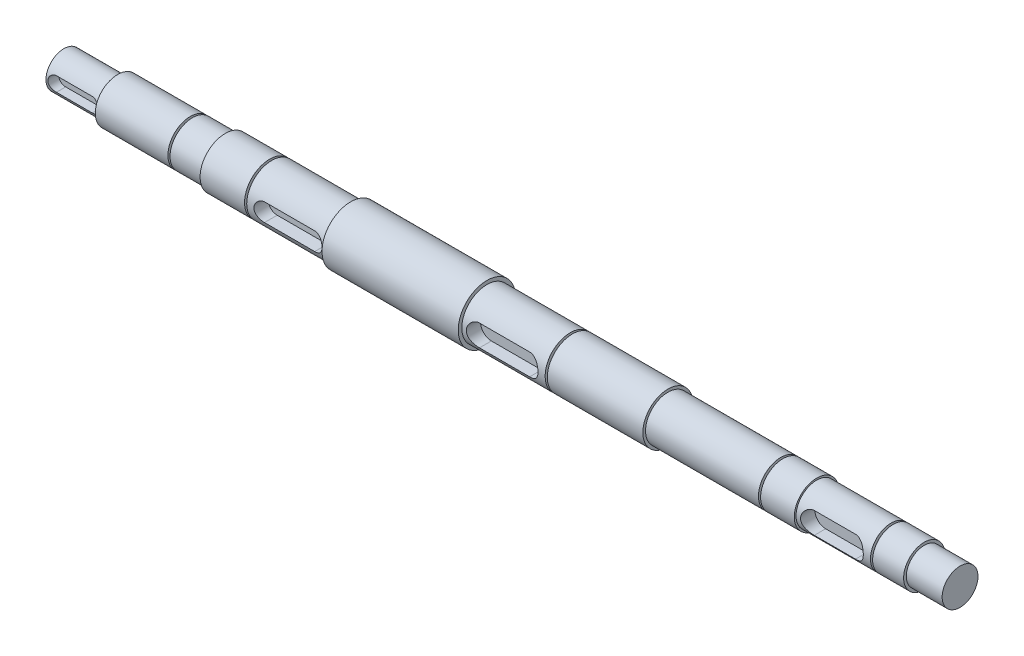
SolidWorks part; units mm, degrees
ref_plane "Front Plane" through (0, 0, 0) normal (0, 0, 1) x (1, 0, 0)
ref_plane "Top Plane" through (0, 0, 0) normal (0, 1, 0) x (1, 0, 0)
ref_plane "Right Plane" through (0, 0, 0) normal (1, 0, 0) x (0, 0, -1)
sketch "Sketch1" plane through (0, 0, 0) normal (1, 0, 0) x (0, 0, -1)
  circle A0 centre (0, 0) radius 10
  dimension "D1" = 20
extrude "Boss-Extrude1" add sketch "Sketch1" along normal blind 30
sketch "Sketch2" plane through (30, 0, 0) normal (1, 0, 0) x (0, 0, -1)
  circle A0 centre (0, 0) radius 12.5
  circle A2 centre (0, 0) radius 10 construction
  dimension "D1" = 25
extrude "Boss-Extrude5" add sketch "Sketch2" along normal blind 60
sketch "Sketch5" plane through (90, 0, 0) normal (1, 0, 0) x (0, 0, -1)
  circle A0 centre (0, 0) radius 14
  dimension "D1" = 28
extrude "Boss-Extrude8" add sketch "Sketch5" along normal blind 70
sketch "Sketch7" plane through (160, 0, 0) normal (1, 0, 0) x (0, 0, -1)
  circle A0 centre (0, 0) radius 16
  dimension "D1" = 32
extrude "Boss-Extrude9" add sketch "Sketch7" along normal blind 76
sketch "Sketch8" plane through (236, 0, 0) normal (1, 0, 0) x (0, 0, -1)
  circle A0 centre (0, 0) radius 14
  dimension "D1" = 28
extrude "Boss-Extrude13" add sketch "Sketch8" along normal blind 24
sketch "Sketch12" plane through (260, 0, 0) normal (1, 0, 0) x (0, 0, -1)
  circle A0 centre (0, 0) radius 12.5
  dimension "D1" = 25
extrude "Boss-Extrude15" add sketch "Sketch12" along normal blind 150
sketch "Sketch14" plane through (410, 0, 0) normal (1, 0, 0) x (0, 0, -1)
  circle A0 centre (0, 0) radius 11.5
  dimension "D1" = 23
extrude "Boss-Extrude16" add sketch "Sketch14" along normal blind 70
sketch "Sketch15" plane through (480, 0, 0) normal (1, 0, 0) x (0, 0, -1)
  circle A1 centre (0, 0) radius 10
  dimension "D1" = 20
extrude "Boss-Extrude17" add sketch "Sketch15" along normal blind 20
ref_plane "Plane1" through (0, 0, 10) normal (0, 0, 1) x (1, 0, 0)
sketch "Sketch16" plane through (0, 0, 10) normal (0, 0, 1) x (1, 0, 0)
  line L0 (0, 0) -> (30, 0) construction
  line L1 (30, 12.5) -> (30, -12.5) construction
  line L2 (5, 0) -> (25, 0) construction
  line L3 (5, 4) -> (25, 4)
  line L4 (5, -4) -> (25, -4)
  arc A0 (5, 4) -> (5, -4) centre (5, 0) ccw
  arc A1 (25, -4) -> (25, 4) centre (25, 0) ccw
  point P7 (15, 0)
  dimension "D1" = 20
  dimension "D2" = 5
  dimension "D3" = 8
extrude "Cut-Extrude1" cut sketch "Sketch16" against normal blind 6
ref_plane "Plane2" through (0, 0, 14) normal (0, 0, 1) x (1, 0, 0)
sketch "Sketch17" plane through (0, 0, 14) normal (0, 0, 1) x (1, 0, 0)
  line L0 (90, 0) -> (160, 0) construction
  line L1 (90, 14) -> (90, -14) construction
  line L2 (160, 16) -> (160, -16) construction
  line L3 (125, 0) -> (153, 0) construction
  line L4 (125, 5) -> (153, 5)
  line L5 (125, -5) -> (153, -5)
  arc A0 (125, 5) -> (125, -5) centre (125, 0) ccw
  arc A1 (153, -5) -> (153, 5) centre (153, 0) ccw
  point P8 (139, 0)
  dimension "D1" = 28
  dimension "D2" = 35
  dimension "D3" = 10
extrude "Cut-Extrude2" cut sketch "Sketch17" against normal blind 8
sketch "Sketch18" plane through (236, 0, 0) normal (1, 0, 0) x (0, 0, -1)
  circle A0 centre (0, 0) radius 14
extrude "Cut-Extrude3" cut sketch "Sketch18" along normal up to surface (264 mm away) up to face at (500, 0, -10)
sketch "Sketch19" plane through (236, 0, 0) normal (1, 0, 0) x (0, 0, -1)
  circle A0 centre (0, 0) radius 14
  dimension "D1" = 28
extrude "Boss-Extrude18" add sketch "Sketch19" along normal blind 45
sketch "Sketch20" plane through (281, 0, 0) normal (1, 0, 0) x (0, 0, -1)
  circle A0 centre (0, 0) radius 12.5
  dimension "D1" = 25
extrude "Boss-Extrude19" add sketch "Sketch20" along normal blind 139
sketch "Sketch21" plane through (420, 0, 0) normal (1, 0, 0) x (0, 0, -1)
  circle A0 centre (0, 0) radius 11.5
  dimension "D1" = 23
extrude "Boss-Extrude20" add sketch "Sketch21" along normal blind 60
sketch "Sketch22" plane through (480, 0, 0) normal (1, 0, 0) x (0, 0, -1)
  circle A0 centre (0, 0) radius 10
  dimension "D1" = 20
extrude "Boss-Extrude21" add sketch "Sketch22" along normal blind 20
ref_plane "Plane3" through (0, 0, 14) normal (0, 0, 1) x (1, 0, 0)
sketch "Sketch24" plane through (0, 0, 14) normal (0, 0, 1) x (1, 0, 0)
  line L0 (236, 0) -> (281, 0) construction
  line L1 (236, -16) -> (236, 16) construction
  line L2 (281, -12.5) -> (281, 12.5) construction
  line L3 (244.5, 0) -> (272.5, 0) construction
  line L4 (244.5, 6) -> (272.5, 6)
  line L5 (244.5, -6) -> (272.5, -6)
  arc A0 (244.5, 6) -> (244.5, -6) centre (244.5, 0) ccw
  arc A1 (272.5, -6) -> (272.5, 6) centre (272.5, 0) ccw
  point P8 (258.5, 0)
  dimension "D1" = 28
  dimension "D2" = 8.5
  dimension "D3" = 12
extrude "Cut-Extrude4" cut sketch "Sketch24" against normal blind 8
ref_plane "Plane4" through (0, 0, 11.5) normal (0, 0, 1) x (1, 0, 0)
sketch "Sketch25" plane through (0, 0, 11.5) normal (0, 0, 1) x (1, 0, 0)
  line L0 (420, 0) -> (480, 0) construction
  line L1 (420, -11.5) -> (420, 11.5) construction
  line L2 (480, -10) -> (480, 10) construction
  line L3 (428.5, 0) -> (451.5, 0) construction
  line L4 (428.5, 6) -> (451.5, 6)
  line L5 (428.5, -6) -> (451.5, -6)
  arc A0 (428.5, 6) -> (428.5, -6) centre (428.5, 0) ccw
  arc A1 (451.5, -6) -> (451.5, 6) centre (451.5, 0) ccw
  point P8 (440, 0)
  dimension "D1" = 23
  dimension "D2" = 8.5
  dimension "D3" = 12
extrude "Cut-Extrude5" cut sketch "Sketch25" against normal blind 8
sketch "Sketch26" plane through (0, 0, 0) normal (0, 1, 0) x (1, 0, 0)
  line L0 (30.472, 0) -> (90.5336, 0) construction
  line L1 (90.5336, 0) -> (70.5336, 0)
  line L2 (70.5336, -12.5) -> (70.5336, -10.7)
  line L3 (30, -12.5) -> (90, -12.5) construction
  line L4 (70.5336, -10.7) -> (71.7336, -10.7)
  line L5 (71.7336, -10.7) -> (71.7336, -12.5)
  line L6 (71.7336, -12.5) -> (70.5336, -12.5)
  dimension "D1" = 20
  dimension "D2" = 1.2
  dimension "D3" = 1.8
revolve "Cut-Revolve2" cut sketch "Sketch26" angle 360 about L0
sketch "Sketch27" plane through (0, 0, 0) normal (0, 1, 0) x (1, 0, 0)
  line L5 (114.8, -14) -> (114.8, -12.2)
  line L6 (90, -14) -> (120, -14) construction
  line L7 (114.8, -12.2) -> (116, -12.2)
  line L8 (116, -12.2) -> (116, -14)
  line L9 (116, -14) -> (114.8, -14)
  line L10 (162, -14) -> (162, -12.2)
  line L11 (158, -14) -> (160, -14) construction
  line L12 (162, -12.2) -> (163.2, -12.2)
  line L13 (163.2, -12.2) -> (163.2, -14)
  line L14 (90.3, 0) -> (160.6697, 0) construction
  line L15 (162, -14) -> (163.2, -14)
  dimension "D1" = 1.8
  dimension "D2" = 1.2
  dimension "D3" = 4
  dimension "D4" = 4
  dimension "D5" = 1.8
  dimension "D6" = 1.2
sketch "Sketch29" plane through (0, 0, 0) normal (0, 1, 0) x (1, 0, 0)
  line L0 (282.5799, 0) -> (419.736, 0) construction
sketch "Sketch30" plane through (0, 0, 0) normal (0, 1, 0) x (1, 0, 0)
  line L0 (461.5, -11.5) -> (461.5, -9.7)
  line L1 (457.5, -11.5) -> (480, -11.5) construction
  line L2 (461.5, -9.7) -> (462.7, -9.7)
  line L3 (462.7, -9.7) -> (462.7, -11.5)
  line L4 (462.7, -11.5) -> (461.5, -11.5)
  line L5 (419.736, 0) -> (479.6335, 0) construction
  dimension "D1" = 4
  dimension "D2" = 1.2
  dimension "D3" = 1.8
revolve "Cut-Revolve5" cut sketch "Sketch30" angle 360 about L5
sketch "Sketch31" plane through (0, 0, 0) normal (0, 1, 0) x (1, 0, 0)
  line L0 (419.736, 0) -> (371.6358, 0) construction
  line L1 (282.5799, 0) -> (419.736, 0) construction
  line L2 (400, -12.5) -> (400, -10.7)
  line L3 (281, -12.5) -> (420, -12.5) construction
  line L4 (420, -12.5) -> (420, 12.5) construction
  line L5 (400, -10.7) -> (401.2, -10.7)
  line L6 (401.2, -10.7) -> (401.2, -12.5)
  line L7 (401.2, -12.5) -> (400, -12.5)
  dimension "D1" = 20
  dimension "D2" = 1.2
  dimension "D3" = 1.8
revolve "Cut-Revolve6" cut sketch "Sketch31" angle 360 about L0
sketch "Sketch32" plane through (0, 0, 0) normal (0, 1, 0) x (1, 0, 0)
  line L10 (282.5799, 0) -> (379.819, 0) construction
  line L11 (282.5799, 0) -> (419.736, 0) construction
sketch "Sketch34" plane through (0, 0, 0) normal (0, 1, 0) x (1, 0, 0)
  line L2 (116, -14) -> (116, -12.2)
  line L3 (90, -14) -> (120.0001, -14) construction
  line L4 (116, -12.2) -> (114.8, -12.2)
  line L6 (120, -14) -> (120, -12.1326)
  line L7 (114.8, -12.2) -> (114.8, -14)
  line L8 (91.0011, 0) -> (162.6801, 0) construction
  line L9 (90.3, 0) -> (160.6697, 0) construction
  line L10 (116, -14) -> (114.8, -14)
  dimension "D1" = 4
  dimension "D2" = 1.8
  dimension "D3" = 1.2
revolve "Cut-Revolve8" cut sketch "Sketch34" angle 360 about L8
sketch "Sketch35" plane through (281, 0, 0) normal (1, 0, 0) x (0, 0, -1)
  circle A0 centre (0, 0) radius 14
extrude "Boss-Extrude22" add sketch "Sketch35" along normal blind 56
sketch "Sketch36" plane through (0, 0, 0) normal (0, 1, 0) x (1, 0, 0)
  line L0 (235.1662, 0) -> (336.4456, 0) construction
  line L1 (282.5799, 0) -> (379.819, 0) construction
  line L2 (282.5, -14) -> (282.5, -12.2)
  line L3 (278.4999, -14) -> (337, -14) construction
  line L4 (282.5, -12.2) -> (283.7, -12.2)
  line L5 (283.7, -12.2) -> (283.7, -14)
  line L6 (283.7, -14) -> (282.5, -14)
  dimension "D1" = 4
  dimension "D2" = 1.2
  dimension "D3" = 1.8
revolve "Cut-Revolve9" cut sketch "Sketch36" angle 360 about L0
